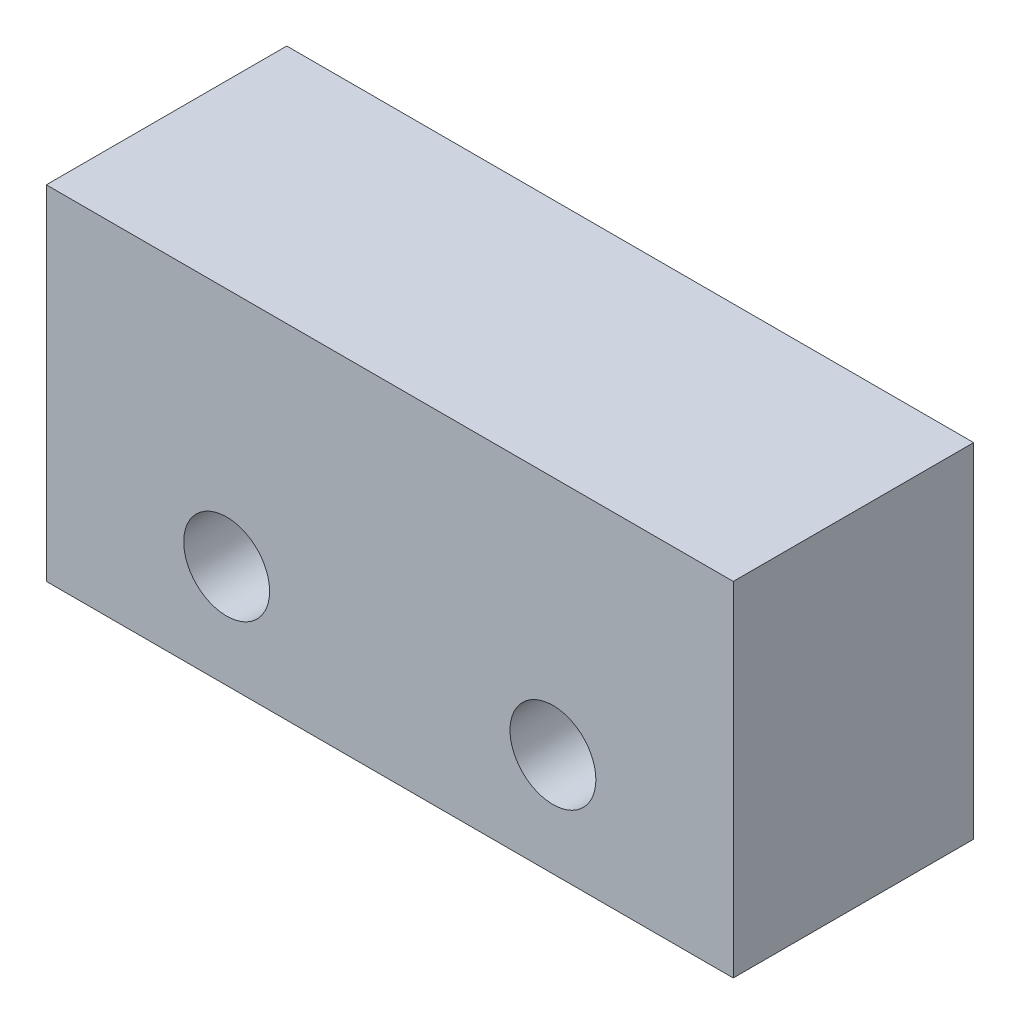
SolidWorks part; units mm, degrees
ref_plane "Front Plane" through (0, 0, 0) normal (0, 0, 1) x (1, 0, 0)
ref_plane "Top Plane" through (0, 0, 0) normal (0, 1, 0) x (1, 0, 0)
ref_plane "Right Plane" through (0, 0, 0) normal (1, 0, 0) x (0, 0, -1)
sketch "Croquis1" plane through (0, 0, 0) normal (0, 1, 0) x (1, 0, 0)
  line L1 (-10, 3.5) -> (10, 3.5)
  line L2 (-10, 3.5) -> (-10, -3.5)
  line L3 (-10, -3.5) -> (10, -3.5)
  line L4 (10, 3.5) -> (10, -3.5)
  line L5 (-10, 3.5) -> (10, -3.5) construction
  line L6 (-10, -3.5) -> (10, 3.5) construction
  point P0 (0, 0)
  dimension "D1" = 7
  dimension "D2" = 20
extrude "Saliente-Extruir1" add sketch "Croquis1" along normal blind 10
hole_wizard "Taladro1" positions "Croquis2" profile "Croquis3" legacy end condition through all
sketch "Croquis2" plane through (0, 0, 3.5) normal (0, 0, 1) x (1, 0, 0)
  line L0 (-4.75, 3) -> (4.75, 3)
  point P1 (-4.75, 3)
  point P2 (4.75, 3)
  point P10 (0, 3)
  dimension "D1" = 9.5
  dimension "D2" = 3
sketch "Croquis3" plane through (-4.75, 3, 3.5) normal (1, 0, 0) x (0, -1, 0)
  line L0 (0, 0) -> (0, 7)
  line L1 (0, 7) -> (1.25, 7)
  line L2 (1.25, 7) -> (1.25, 0)
  line L3 (1.25, 0) -> (0, 0)
  line L4 (0, 110) -> (0, -10) construction
  dimension "Diámetro" = 2.5
  dimension "Profundidad" = 7
